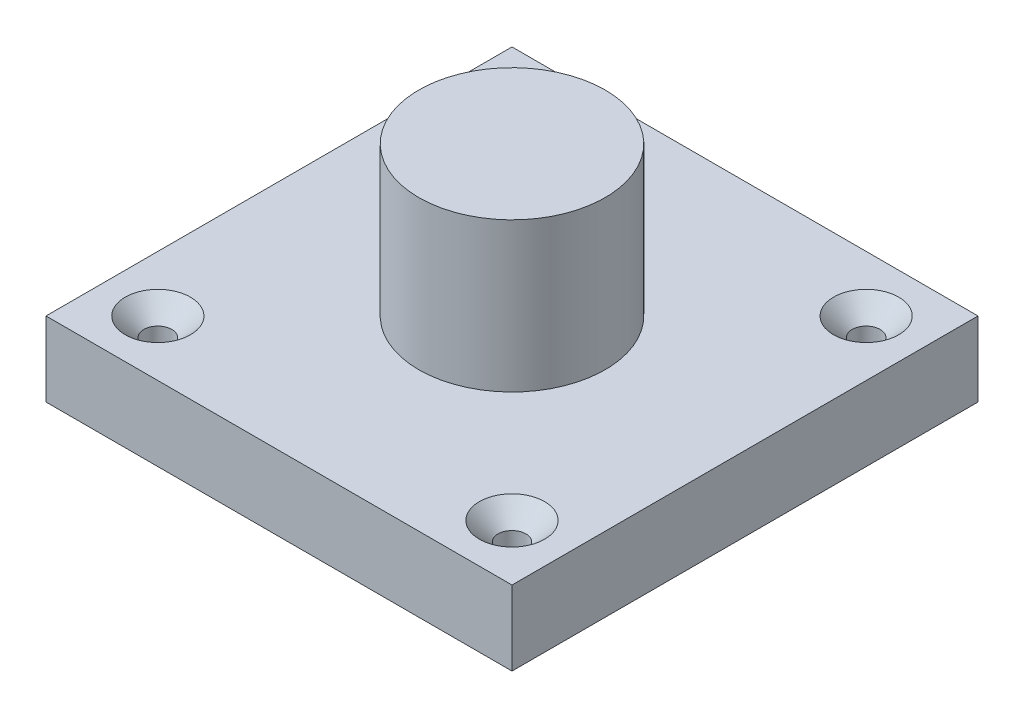
SolidWorks part; units mm, degrees
ref_plane "Front Plane" through (0, 0, 0) normal (0, 0, 1) x (1, 0, 0)
ref_plane "Top Plane" through (0, 0, 0) normal (0, 1, 0) x (1, 0, 0)
ref_plane "Right Plane" through (0, 0, 0) normal (1, 0, 0) x (0, 0, -1)
sketch "Sketch1" plane through (0, 0, 0) normal (0, 1, 0) x (1, 0, 0)
  line L1 (-25, -25) -> (25, -25)
  line L2 (-25, -25) -> (-25, 25)
  line L3 (-25, 25) -> (25, 25)
  line L4 (25, -25) -> (25, 25)
  line L5 (-25, -25) -> (25, 25) construction
  line L6 (-25, 25) -> (25, -25) construction
  point P0 (0, 0)
  dimension "D1" = 50
  dimension "D2" = 50
extrude "Boss-Extrude1" add sketch "Sketch1" along normal blind 8
sketch "Sketch2" plane through (0, 8, 0) normal (0, 1, 0) x (1, 0, 0)
  circle A0 centre (0, 0) radius 10
  dimension "D1" = 20
extrude "Boss-Extrude2" add sketch "Sketch2" along normal blind 16
sketch "Sketch3" plane through (0, 8, 0) normal (0, 1, 0) x (1, 0, 0)
  line L0 (-25, 25) -> (-25, -25) construction
  line L1 (-25, -25) -> (25, -25) construction
  circle A0 centre (-19, -19) radius 1.5
  dimension "D1" = 3
  dimension "D2" = 6
  dimension "D3" = 6
extrude "Cut-Extrude1" cut sketch "Sketch3" against normal blind 8
chamfer "Chamfer1" distance 2 distance2 2 1 edges at (-19, 8, 20.5)
pattern_circular "CirPattern3" count 4 over 360 about axis through (0, 0, 0) along (0, 1, 0) of "Cut-Extrude1", "Chamfer1"
